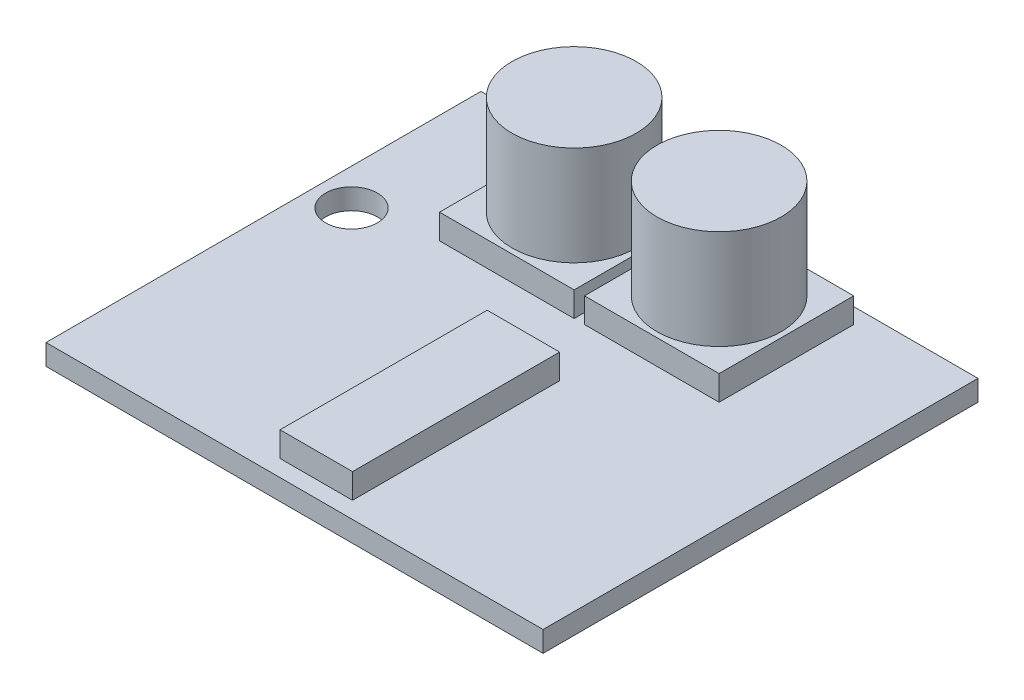
SolidWorks part; units mm, degrees
ref_plane "Front Plane" through (0, 0, 0) normal (0, 0, 1) x (1, 0, 0)
ref_plane "Top Plane" through (0, 0, 0) normal (0, 1, 0) x (1, 0, 0)
ref_plane "Right Plane" through (0, 0, 0) normal (1, 0, 0) x (0, 0, -1)
sketch "Sketch1" plane through (0, 0, 0) normal (0, 1, 0) x (1, 0, 0)
  line L1 (12, -10.5) -> (-12, -10.5)
  line L2 (12, -10.5) -> (12, 10.5)
  line L3 (12, 10.5) -> (-12, 10.5)
  line L4 (-12, -10.5) -> (-12, 10.5)
  line L5 (12, -10.5) -> (-12, 10.5) construction
  line L6 (12, 10.5) -> (-12, -10.5) construction
  circle A0 centre (-10.25, 2.5) radius 1.25
  point P0 (0, 0)
  dimension "D4" = 2.5
  dimension "D1" = 24
  dimension "D2" = 21
  dimension "D3" = 8
  dimension "D5" = 1.75
extrude "Boss-Extrude1" add sketch "Sketch1" along normal blind 1
sketch "Sketch2" plane through (0, 1, 0) normal (0, 1, 0) x (1, 0, 0)
  line L0 (12, -10.5) -> (12, 10.5) construction
  line L1 (12, 10.5) -> (-12, 10.5) construction
  circle A0 centre (3.5, 6.5) radius 3
  circle A1 centre (-3.5, 6.5) radius 3
  point P6 (0, 0)
  point P7 (0, 0)
  point P8 (0, 0)
  dimension "D3" = 6
  dimension "D4" = 6
  dimension "D1" = 8.5
  dimension "D2" = 7
  dimension "D5" = 4
extrude "Boss-Extrude2" add sketch "Sketch2" along normal blind 6
sketch "Sketch3" plane through (0, 1, 0) normal (0, 1, 0) x (1, 0, 0)
  line L0 (-12, 10.5) -> (-12, -10.5) construction
  line L1 (-0.25, 3.25) -> (-6.75, 3.25)
  line L2 (-0.25, 3.25) -> (-0.25, 9.75)
  line L3 (-0.25, 9.75) -> (-6.75, 9.75)
  line L4 (-6.75, 3.25) -> (-6.75, 9.75)
  line L5 (-0.25, 3.25) -> (-6.75, 9.75) construction
  line L6 (-0.25, 9.75) -> (-6.75, 3.25) construction
  line L7 (6.75, 3.25) -> (0.25, 3.25)
  line L8 (6.75, 3.25) -> (6.75, 9.75)
  line L9 (6.75, 9.75) -> (0.25, 9.75)
  line L10 (0.25, 3.25) -> (0.25, 9.75)
  line L11 (6.75, 3.25) -> (0.25, 9.75) construction
  line L12 (6.75, 9.75) -> (0.25, 3.25) construction
  line L13 (-1.5, -9.7) -> (2, -9.7)
  line L14 (-1.5, -9.7) -> (-1.5, 0.3)
  line L15 (-1.5, 0.3) -> (2, 0.3)
  line L16 (2, -9.7) -> (2, 0.3)
  line L17 (-12, -10.5) -> (12, -10.5) construction
  point P0 (-3.5, 6.5)
  point P6 (3.5, 6.5)
  dimension "D1" = 6.5
  dimension "D2" = 6.5
  dimension "D3" = 6.5
  dimension "D4" = 6.5
  dimension "D5" = 10.5
  dimension "D6" = 3.5
  dimension "D7" = 10
  dimension "D8" = 0.8
extrude "Boss-Extrude3" add sketch "Sketch3" along normal blind 1.2
